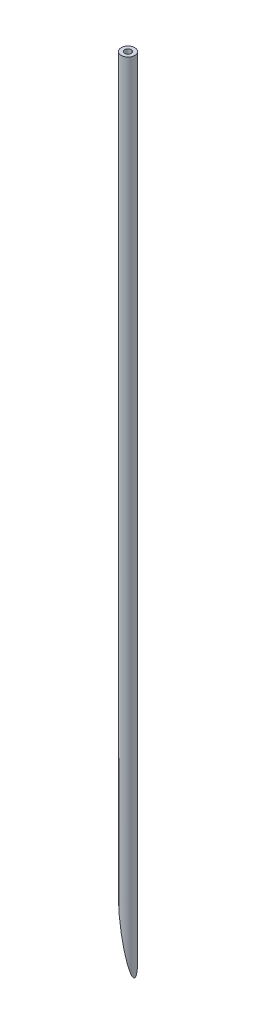
SolidWorks part; units mm, degrees
ref_plane "前视基准面" through (0, 0, 0) normal (0, 0, 1) x (1, 0, 0)
ref_plane "上视基准面" through (0, 0, 0) normal (0, 1, 0) x (1, 0, 0)
ref_plane "右视基准面" through (0, 0, 0) normal (1, 0, 0) x (0, 0, -1)
sketch "草图2" plane through (0, 0, 0) normal (0, 1, 0) x (1, 0, 0)
  circle A0 centre (0, 0) radius 0.255
  circle A1 centre (0, 0) radius 0.125
  dimension "D1" = 0.51
  dimension "D2" = 0.25
extrude "凸台-拉伸1" add sketch "草图2" against normal blind 30
sketch "草图3" plane through (0, 0, 0) normal (0, 0, 1) x (1, 0, 0)
  line L0 (0, -30) -> (0, -78.8031) construction
  line L1 (-0.255, -30) -> (0.255, -30) construction
  line L2 (8.0207, -74.0414) -> (0.255, -30)
  line L3 (8.0207, -74.0414) -> (8.0207, -80.9404)
  line L4 (8.0207, -80.9404) -> (0.255, -80.9404)
  line L6 (0.255, -30) -> (-0.296, -26.8751)
  line L7 (-0.296, -26.8751) -> (-0.296, -80.9404)
  line L8 (-0.296, -80.9404) -> (0.255, -80.9404)
  point P8 (0.255, -30)
  dimension "D1" = 10
extrude "切除-拉伸1" cut sketch "草图3" against normal blind 10 and the other way blind 11
